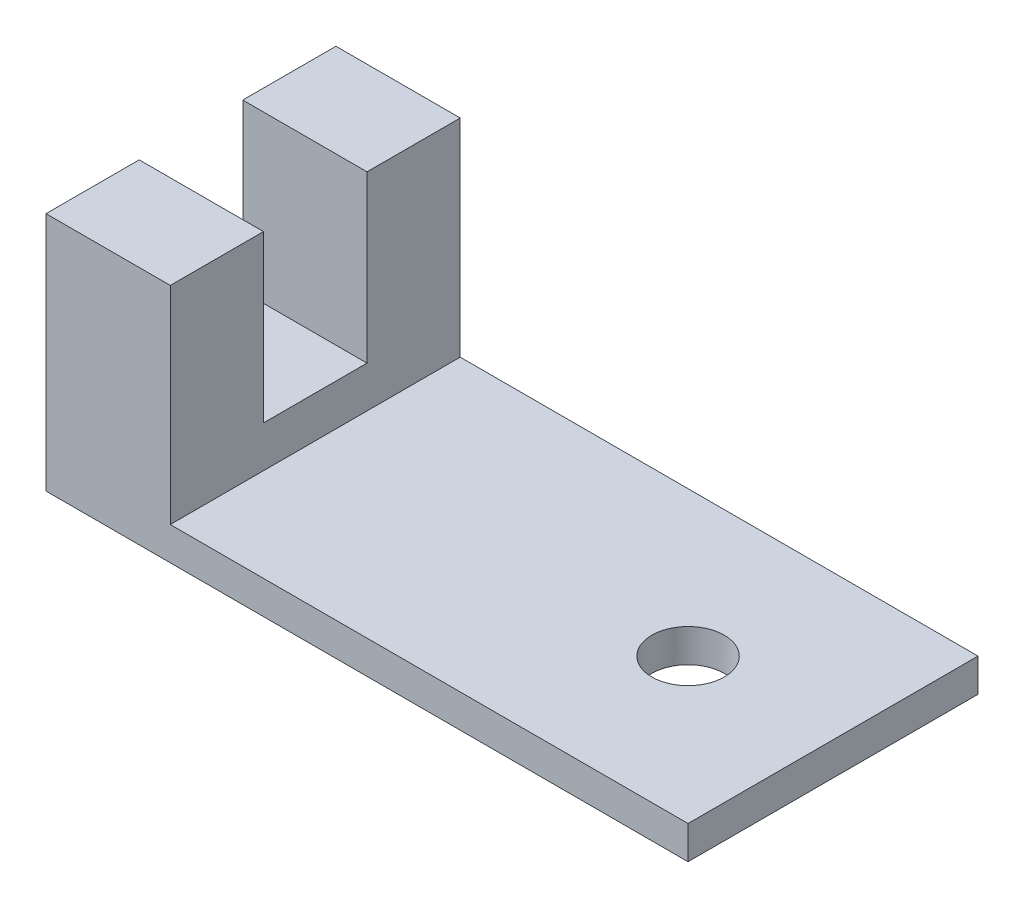
SolidWorks part; units mm, degrees
ref_plane "Piano frontale" through (0, 0, 0) normal (0, 0, 1) x (1, 0, 0)
ref_plane "Piano superiore" through (0, 0, 0) normal (0, 1, 0) x (1, 0, 0)
ref_plane "Piano destro" through (0, 0, 0) normal (1, 0, 0) x (0, 0, -1)
sketch "Schizzo2" plane through (0, 0, 0) normal (0, 1, 0) x (1, 0, 0)
  line L1 (0, 0) -> (31, 0)
  line L2 (0, 0) -> (0, 14)
  line L3 (0, 14) -> (31, 14)
  line L4 (31, 0) -> (31, 14)
  dimension "D1" = 31
  dimension "D2" = 14
extrude "Estrusione-Estrusione1" add sketch "Schizzo2" along normal blind 1.6
sketch "Schizzo3" plane through (0, 0, 0) normal (-1, 0, 0) x (0, 0, 1)
  line L0 (-14, 1.6) -> (-14, 11.6)
  line L1 (-14, 11.6) -> (-9.5, 11.6)
  line L2 (-9.5, 11.6) -> (-9.5, 3.6)
  line L3 (-9.5, 3.6) -> (-4.5, 3.6)
  line L4 (-4.5, 3.6) -> (-4.5, 11.6)
  line L5 (-4.5, 11.6) -> (0, 11.6)
  line L6 (0, 11.6) -> (0, 1.6)
  line L7 (0, 1.6) -> (-14, 1.6)
  dimension "D1" = 5
  dimension "D2" = 4.5
  dimension "D3" = 8
  dimension "D4" = 10
extrude "Estrusione-Estrusione2" add sketch "Schizzo3" against normal blind 6
sketch "Schizzo4" plane through (0, 1.6, 0) normal (0, 1, 0) x (1, 0, 0)
  line L0 (31, 0) -> (31, 14) construction
  circle A0 centre (24, 7) radius 1.75
  point P2 (0, 0)
  point P3 (0, 0)
  point P6 (0, 0)
  point P7 (0, 0)
  point P8 (31, 7)
  dimension "D1" = 3.5
  dimension "D6" = 7
extrude "Taglio-Estrusione1" cut sketch "Schizzo4" against normal up to next
